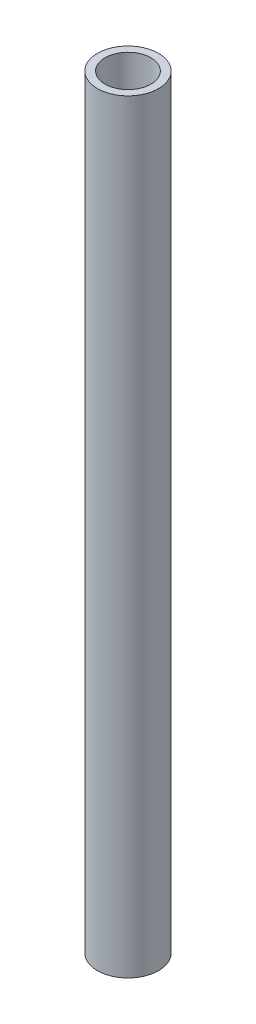
SolidWorks part; units mm, degrees
ref_plane "Front Plane" through (0, 0, 0) normal (0, 0, 1) x (1, 0, 0)
ref_plane "Top Plane" through (0, 0, 0) normal (0, 1, 0) x (1, 0, 0)
ref_plane "Right Plane" through (0, 0, 0) normal (1, 0, 0) x (0, 0, -1)
sketch "Sketch1" plane through (0, 0, 0) normal (0, 0, 1) x (1, 0, 0)
  line L0 (0, 0) -> (0, 100)
  point P6 (0, 100)
  dimension "D1" = 100
sketch "Sketch2" plane through (0, 0, 0) normal (0, 1, 0) x (1, 0, 0)
  circle A0 centre (0, 0) radius 4
  circle A1 centre (0, 0) radius 3
  dimension "D1" = 6
  dimension "D2" = 8
sweep "Sweep1" add profiles "Sketch2" path "Sketch1"
